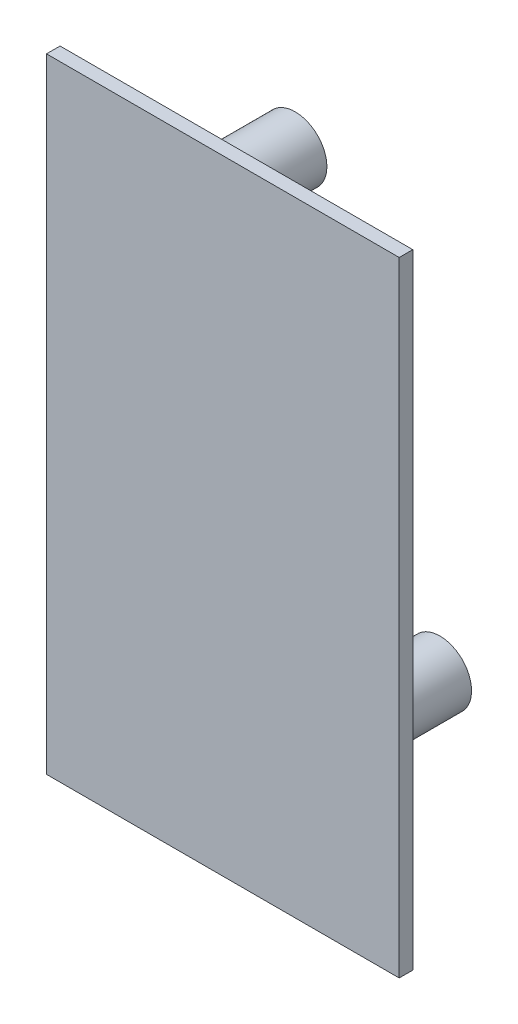
SolidWorks part; units mm, degrees
ref_plane "Спереди" through (0, 0, 0) normal (0, 0, 1) x (1, 0, 0)
ref_plane "Сверху" through (0, 0, 0) normal (0, 1, 0) x (1, 0, 0)
ref_plane "Справа" through (0, 0, 0) normal (1, 0, 0) x (0, 0, -1)
sketch "Эскиз1" plane through (0, 0, 0) normal (0, 0, 1) x (1, 0, 0)
  line L1 (0, 0) -> (39, 0)
  line L2 (0, 0) -> (0, 69)
  line L3 (0, 69) -> (39, 69)
  line L4 (39, 0) -> (39, 69)
  dimension "D1" = 69
  dimension "D2" = 39
extrude "Бобышка-Вытянуть1" add sketch "Эскиз1" along normal blind 1.5
sketch "Эскиз2" plane through (0, 0, 0) normal (0, 0, -1) x (-1, 0, 0)
  line L0 (-19, 69) -> (-19, 0) construction
  line L1 (-19, 65.2) -> (-19, 12.2) construction
  line L2 (0, 0) -> (-39, 0) construction
  line L4 (-19, 65.2) -> (-19, 69) construction
  line L5 (-39, 69) -> (0, 69) construction
  line L6 (-19, 69) -> (-19, 65.2) construction
  line L7 (-19, 65.2) -> (0, 65.2) construction
  line L8 (0, 69) -> (0, 0) construction
  line L9 (-39, 0) -> (-39, 69) construction
  circle A0 centre (-35, 23) radius 1.5
  circle A1 centre (-19, 12.2) radius 1.5
  circle A2 centre (-19, 65.2) radius 1.5
  circle A5 centre (-19, 65.2) radius 3.5
  circle A6 centre (-35, 23) radius 3.5
  circle A7 centre (-19, 12.2) radius 3.5
  point P14 (0, 0)
  point P22 (-19, 65.2)
  point P23 (-34.2967, 16.2375)
  dimension "D1" = 20
  dimension "D6" = 23
  dimension "D2" = 7
  dimension "D3" = 3
  dimension "D4" = 3.8
  dimension "D5" = 53
  dimension "D7" = 4
extrude "Бобышка-Вытянуть2" add sketch "Эскиз2" along normal blind 7
